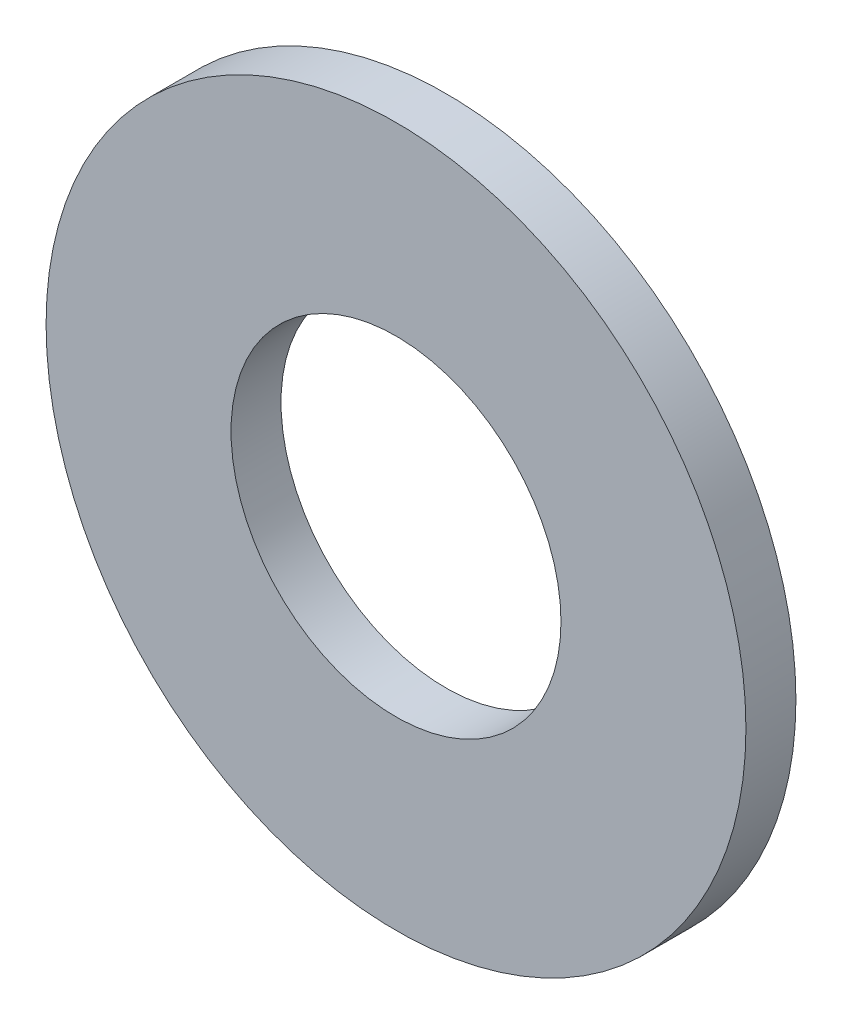
SolidWorks part; units mm, degrees
ref_plane "前视基准面" through (0, 0, 0) normal (0, 0, 1) x (1, 0, 0)
ref_plane "上视基准面" through (0, 0, 0) normal (0, 1, 0) x (1, 0, 0)
ref_plane "右视基准面" through (0, 0, 0) normal (1, 0, 0) x (0, 0, -1)
other "Configuration Table"
sketch "草图1" plane through (0, 0, 0) normal (0, 0, 1) x (1, 0, 0)
  circle A0 centre (0, 0) radius 3.5
  circle A1 centre (0, 0) radius 1.65
extrude "凸台-拉伸1" add sketch "草图1" along normal mid plane 0.5
